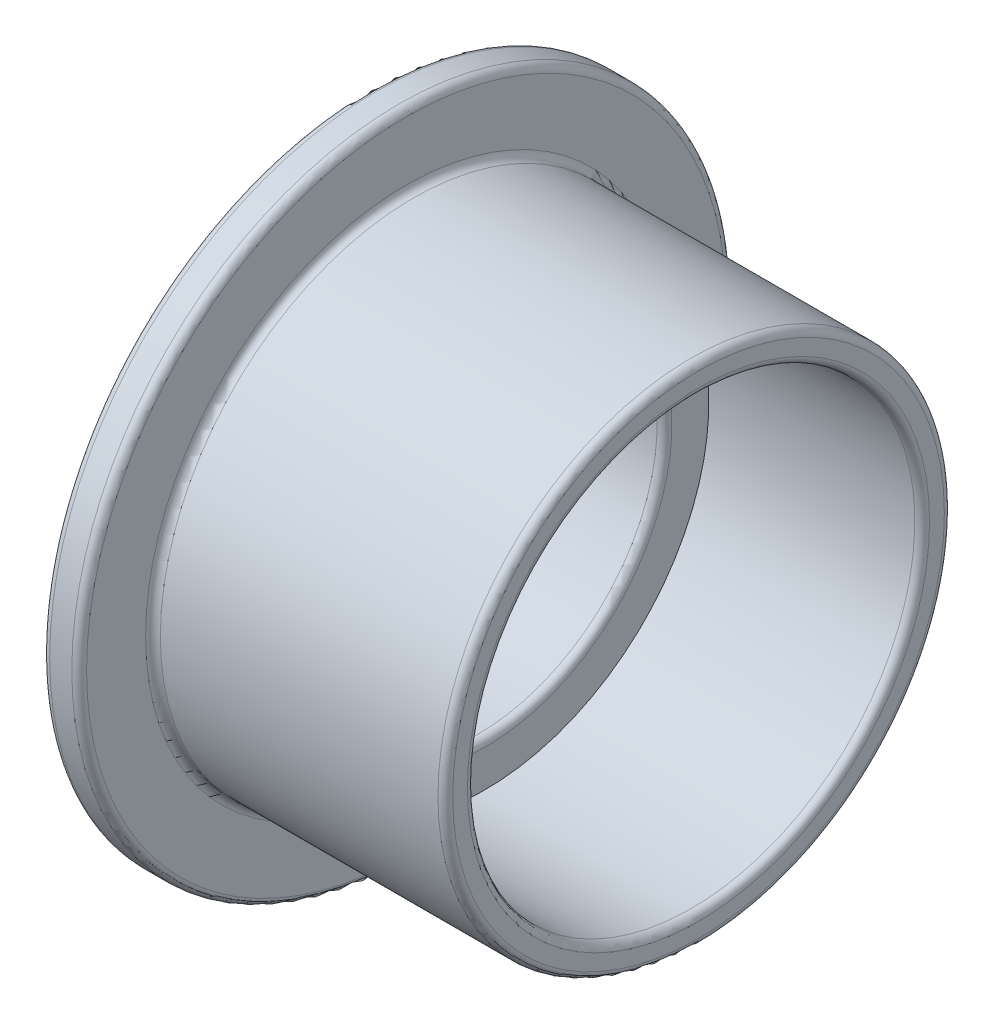
SolidWorks part; units mm, degrees
ref_plane "Front Plane" through (0, 0, 0) normal (0, 0, 1) x (1, 0, 0)
ref_plane "Top Plane" through (0, 0, 0) normal (0, 1, 0) x (1, 0, 0)
ref_plane "Right Plane" through (0, 0, 0) normal (1, 0, 0) x (0, 0, -1)
sketch "Sketch1" plane through (0, 0, 0) normal (0, 0, 1) x (1, 0, 0)
  line L0 (-30.8496, 0) -> (-13.9977, 0) construction
  line L1 (-12.5, 22.15) -> (-12.5, 12.15)
  line L2 (-12.5, 12.15) -> (-4.65, 12.15)
  line L3 (-4.65, 12.15) -> (-4.65, 15.15)
  line L4 (-4.65, 15.15) -> (9.8, 15.15)
  line L5 (9.8, 15.15) -> (9.8, 17.15)
  line L6 (9.8, 17.15) -> (-10, 17.15)
  line L7 (-10, 17.15) -> (-10, 22.15)
  line L8 (-10, 22.15) -> (-12.5, 22.15)
  line L9 (10, 22.15) -> (12.5, 22.15) construction
  line L10 (12.5, 22.15) -> (12.5, 12.15) construction
  line L11 (12.5, 12.15) -> (4.65, 12.15) construction
  line L12 (4.65, 12.15) -> (4.65, 15.15) construction
  line L13 (4.65, 15.15) -> (9.8, 15.15) construction
  line L14 (9.8, 15.15) -> (9.8, 17.15) construction
  line L15 (9.8, 17.15) -> (10, 17.15) construction
  line L16 (10, 17.15) -> (10, 22.15) construction
  line L17 (-4.65, 12.15) -> (4.65, 12.15) construction
  line L18 (-10, 22.15) -> (10, 22.15) construction
  line L19 (0, 0) -> (0, 12.15) construction
  line L20 (0, 22.15) -> (0, 12.15) construction
  dimension "D1" = 20
  dimension "D2" = 2.5
  dimension "D3" = 15.15
  dimension "D4" = 3
  dimension "D5" = 2
  dimension "D6" = 5
  dimension "D7" = 0.2
  dimension "D8" = 9.3
revolve "Revolve1" add sketch "Sketch1" angle 360 about L0
fillet "Fillet1" radius 0.5 7 edges at (-12.5, 0, 22.15) (-4.65, 0, 12.15) (9.8, 0, 17.15) (9.8, 0, 15.15) (-10, 0, 22.15) (-10, 0, 17.15) (-12.5, 0, 12.15)
